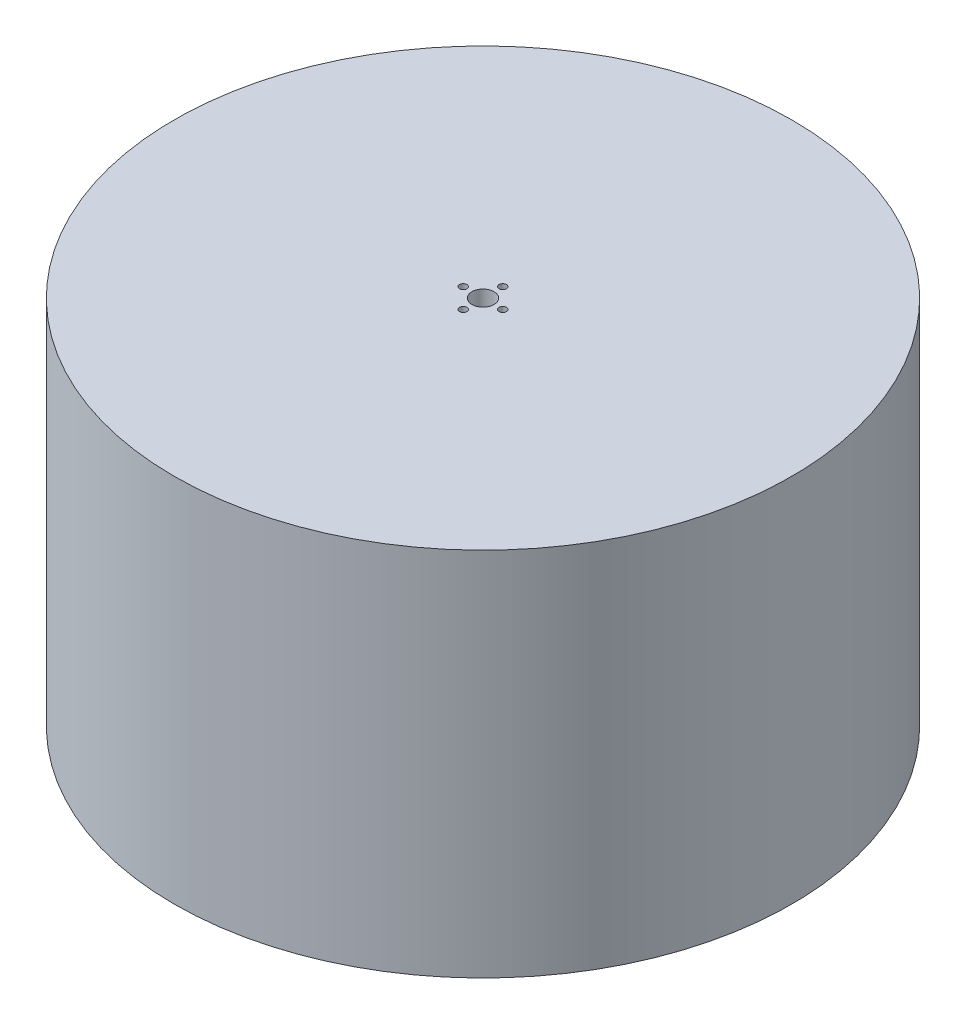
SolidWorks part; units mm, degrees
material "Cast Alloy Steel"
ref_plane "Front Plane" through (0, 0, 0) normal (0, 0, 1) x (1, 0, 0)
ref_plane "Top Plane" through (0, 0, 0) normal (0, 1, 0) x (1, 0, 0)
ref_plane "Right Plane" through (0, 0, 0) normal (1, 0, 0) x (0, 0, -1)
sketch "Sketch1" plane through (0, 0, 0) normal (0, 1, 0) x (1, 0, 0)
  circle A0 centre (0, 0) radius 125
  dimension "D1" = 250
extrude "Boss-Extrude1" add sketch "Sketch1" along normal blind 150
sketch "Sketch2" plane through (0, 0, 0) normal (0, -1, 0) x (1, 0, 0)
  circle A3 centre (0, 0) radius 121
  circle A4 centre (0, 0) radius 121
  dimension "D1" = 4
extrude "Cut-Extrude1" cut sketch "Sketch2" against normal blind 140
sketch "Sketch3" plane through (0, 150, 0) normal (0, 1, 0) x (1, 0, 0)
  circle A0 centre (0, 0) radius 8 construction
  circle A1 centre (-8, 0) radius 1.5
  circle A2 centre (0, 0) radius 4.5
  circle A3 centre (0, 8) radius 1.5
  circle A4 centre (8, 0) radius 1.5
  circle A5 centre (0, -8) radius 1.5
  point P15 (0, 0)
  dimension "D1" = 16
  dimension "D2" = 3
  dimension "D3" = 9
  dimension "D4" = 4
extrude "Cut-Extrude2" cut sketch "Sketch3" against normal through all
